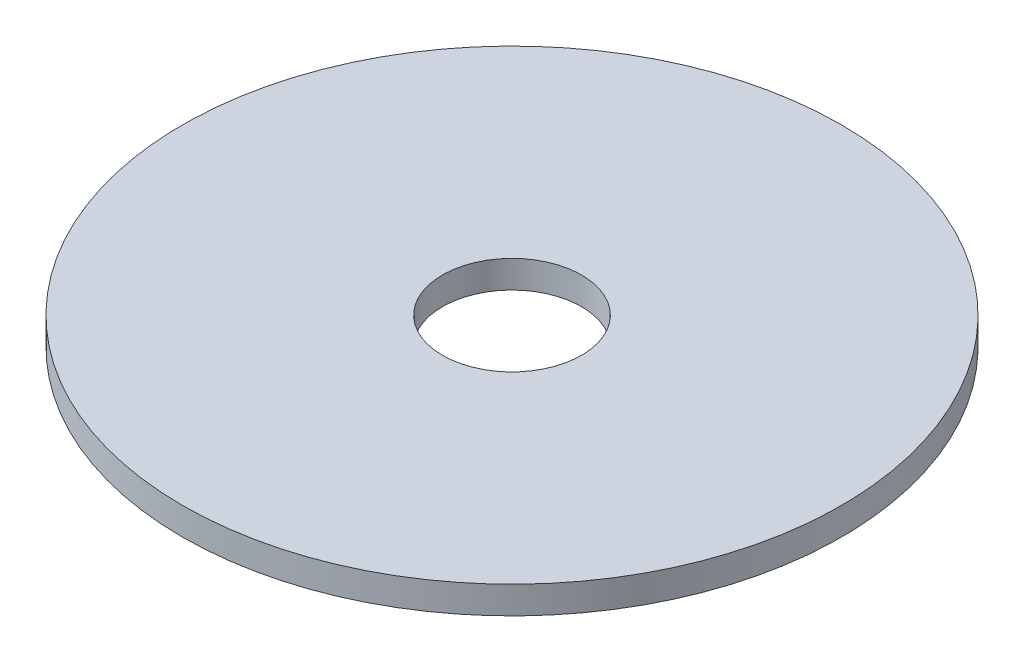
SolidWorks part; units mm, degrees
ref_plane "Спереди" through (0, 0, 0) normal (0, 0, 1) x (1, 0, 0)
ref_plane "Сверху" through (0, 0, 0) normal (0, 1, 0) x (1, 0, 0)
ref_plane "Справа" through (0, 0, 0) normal (1, 0, 0) x (0, 0, -1)
sketch "Эскиз1" plane through (0, 0, 0) normal (0, 1, 0) x (1, 0, 0)
  circle A0 centre (0, 0) radius 36
  circle A1 centre (0, 0) radius 7.6
  dimension "D1" = 15.2
  dimension "D2" = 72
extrude "Вытянуть1" add sketch "Эскиз1" along normal blind 3
